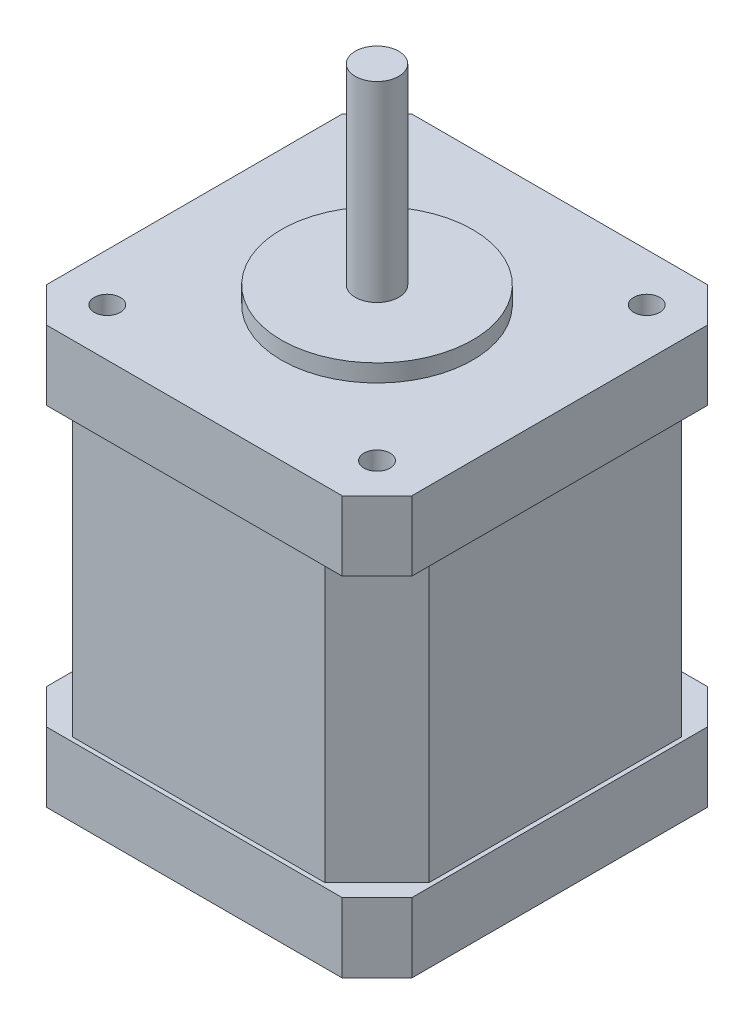
SolidWorks part; units mm, degrees
ref_plane "Front Plane" through (0, 0, 0) normal (0, 0, 1) x (1, 0, 0)
ref_plane "Top Plane" through (0, 0, 0) normal (0, 1, 0) x (1, 0, 0)
ref_plane "Right Plane" through (0, 0, 0) normal (1, 0, 0) x (0, 0, -1)
sketch "Sketch1" plane through (0, 0, 0) normal (0, 1, 0) x (1, 0, 0)
  line L0 (-21, 21) -> (21, -21) construction
  line L1 (-21, 21) -> (21, 21)
  line L2 (-21, 21) -> (-21, -21)
  line L3 (-21, -21) -> (21, -21)
  line L4 (21, 21) -> (21, -21)
  dimension "D1" = 42
extrude "Boss-Extrude1" add sketch "Sketch1" along normal blind 8
pattern_linear "LPattern2" count 2 spacing 40 along (0, -1, 0) of bodies 101
sketch "Sketch5" plane through (0, 0, 0) normal (0, -1, 0) x (1, 0, 0)
  line L8 (-20.5, 20.5) -> (-20.5, -20.5)
  line L9 (-20.5, -20.5) -> (20.5, -20.5)
  line L10 (20.5, -20.5) -> (20.5, 20.5)
  line L11 (20.5, 20.5) -> (-20.5, 20.5)
  line L12 (-20.5, 20.5) -> (-20.5, -20.5)
  line L13 (-20.5, -20.5) -> (20.5, -20.5)
  line L14 (20.5, -20.5) -> (20.5, 20.5)
  line L15 (20.5, 20.5) -> (-20.5, 20.5)
  dimension "D1" = 0.5
extrude "Boss-Extrude4" add sketch "Sketch5" along normal up to next
chamfer "Chamfer2" distance 6 angle 45 4 edges at (20.5, -16, -20.5) (20.5, -16, 20.5) (-20.5, -16, 20.5) (-20.5, -16, -20.5)
chamfer "Chamfer1" distance 4 angle 45 8 edges at (-21, 4, -21) (-21, 4, 21) (21, 4, -21) (21, 4, 21) (-21, -36, -21) (-21, -36, 21) (21, -36, -21) (21, -36, 21)
sketch "Sketch2" plane through (0, 8, 0) normal (0, 1, 0) x (1, 0, 0)
  circle A0 centre (0, 0) radius 11
  dimension "D1" = 22
extrude "Boss-Extrude2" add sketch "Sketch2" along normal blind 2
sketch "Sketch3" plane through (0, 10, 0) normal (0, 1, 0) x (1, 0, 0)
  circle A0 centre (0, 0) radius 2.5
  dimension "D1" = 5
extrude "Boss-Extrude3" add sketch "Sketch3" along normal blind 22
sketch "Sketch6" plane through (0, 8, 0) normal (0, 1, 0) x (1, 0, 0)
  line L0 (-15.5, 15.5) -> (15.5, 15.5) construction
  line L1 (15.5, 15.5) -> (15.5, -15.5) construction
  line L2 (15.5, -15.5) -> (-15.5, -15.5) construction
  line L3 (-15.5, -15.5) -> (-15.5, 15.5) construction
  line L4 (-15.5, 15.5) -> (15.5, -15.5) construction
  circle A0 centre (-15.5, 15.5) radius 1.5
  circle A1 centre (15.5, 15.5) radius 1.5
  circle A2 centre (15.5, -15.5) radius 1.5
  circle A3 centre (-15.5, -15.5) radius 1.5
  dimension "D1" = 3
  dimension "D2" = 31
extrude "Cut-Extrude1" cut sketch "Sketch6" against normal blind 7
